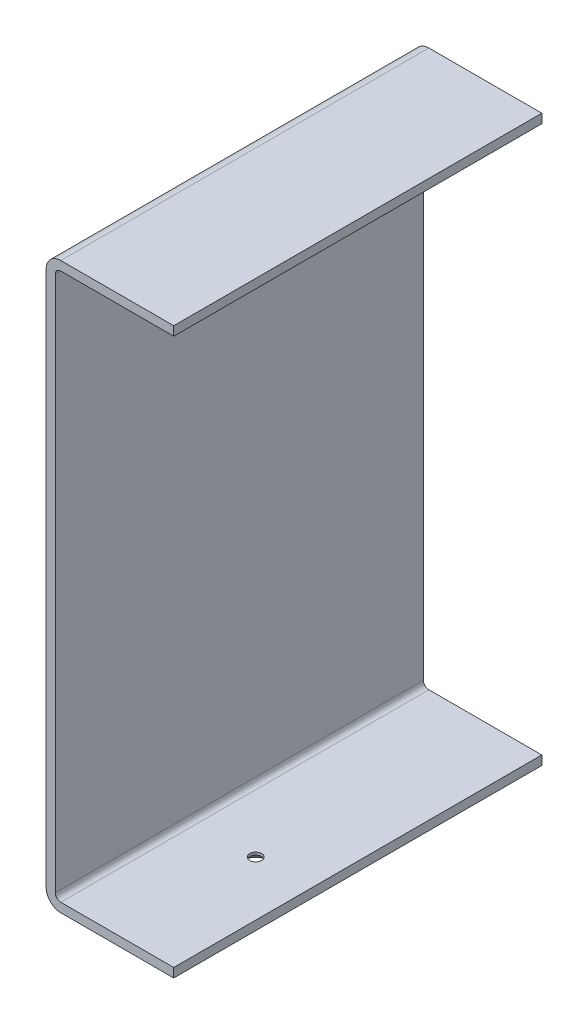
SolidWorks part; units mm, degrees
material "AISI 304"
ref_plane "Спереди" through (0, 0, 0) normal (0, 0, 1) x (1, 0, 0)
ref_plane "Сверху" through (0, 0, 0) normal (0, 1, 0) x (1, 0, 0)
ref_plane "Справа" through (0, 0, 0) normal (1, 0, 0) x (0, 0, -1)
sketch "Эскиз1" plane through (0, 0, 0) normal (0, 0, 1) x (1, 0, 0)
  line L0 (70, 0) -> (8, 0)
  line L1 (0, 8) -> (0, 302)
  line L2 (8, 310) -> (70, 310)
  line L8 (70, 5) -> (8, 5)
  line L9 (5, 8) -> (5, 302)
  line L10 (8, 305) -> (70, 305)
  line L11 (70, 310) -> (70, 305)
  line L12 (70, 5) -> (70, 0)
  arc A0 (0, 302) -> (8, 310) centre (8, 302) cw
  arc A1 (8, 0) -> (0, 8) centre (8, 8) cw
  arc A2 (8, 5) -> (5, 8) centre (8, 8) cw
  arc A3 (5, 302) -> (8, 305) centre (8, 302) cw
  point P9 (0, 0)
  dimension "D2" = 8
  dimension "D3" = 310
  dimension "D1" = 70
  dimension "D4" = 5
extrude "Бобышка-Вытянуть1" add sketch "Эскиз1" along normal blind 202
sketch "Эскиз23" plane through (0, 0, 0) normal (0, -1, 0) x (1, 0, 0)
  line L0 (8, 202) -> (70, 202) construction
  line L1 (70, 202) -> (70, 0) construction
  circle A0 centre (35, 104) radius 8.25
  dimension "D1" = 16.5
  dimension "D2" = 98
  dimension "D3" = 35
extrude "Отверстие шпильки натяжителя" [suppressed] cut sketch "Эскиз23" against normal blind 10
sketch "Эскиз24" plane through (0, 310, 0) normal (0, 1, 0) x (1, 0, 0)
  line L0 (70, -202) -> (70, 0) construction
  line L1 (70, -202) -> (8, -202) construction
  circle A0 centre (35, -181.5) radius 4.1
  dimension "D1" = 8.2
  dimension "D2" = 35
  dimension "D3" = 20.5
extrude "Отверстие крепления крышки 2" [suppressed] cut sketch "Эскиз24" against normal blind 10
sketch "Эскиз25" plane through (0, 0, 0) normal (0, -1, 0) x (1, 0, 0)
  line L0 (70, 202) -> (70, 0) construction
  line L1 (8, 202) -> (70, 202) construction
  point P0 (40, 127)
  dimension "D1" = 30
  dimension "D2" = 75
hole_wizard "Зенковка для винта с потайной головкой и внутренним шестигранником M61" positions "Эскиз25" profile "Эскиз26" countersink size "M6" standard "DIN"
sketch "Эскиз26" plane through (40, 0, 127) normal (1, 0, 0) x (0, 0, -1)
  line L0 (0, 0) -> (0, 11.9828)
  line L1 (0, 11.9828) -> (3.3, 10)
  line L2 (3.3, 10) -> (3.3, 3.555)
  line L3 (3.3, 3.555) -> (6.855, 0)
  line L5 (6.855, 0) -> (0, 0)
  line L6 (-3.3, 3.555) -> (-6.855, 0) construction
  line L10 (0, 11.9828) -> (-3.3, 10) construction
  line L11 (0, -6.35) -> (0, 107.95) construction
  dimension "Диаметр отверстия" = 6.6
  dimension "Глубина отверстия" = 10
  dimension "Диаметр передней зенковки" = 13.71
  dimension "Угол передней зенковки" = 90
  dimension "Угол заточки сверла" = 118
